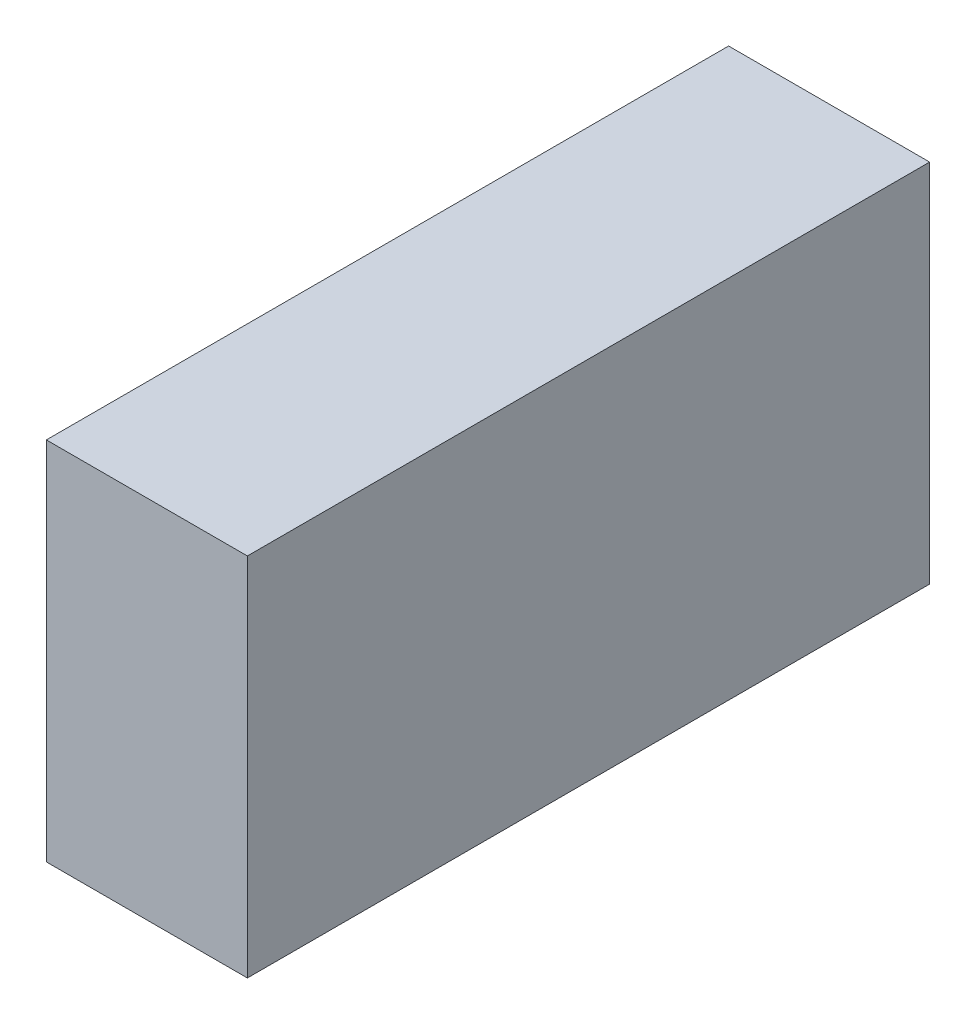
SolidWorks part; units mm, degrees
ref_plane "Front Plane" through (0, 0, 0) normal (1, 0, 0) x (0, 1, 0)
ref_plane "Top Plane" through (0, 0, 0) normal (0, 0, 1) x (0, 1, 0)
ref_plane "Right Plane" through (0, 0, 0) normal (0, 1, 0) x (-1, 0, 0)
sketch "Sketch1" plane through (0, 0, 0) normal (0, 0, 1) x (0, 1, 0)
  line L1 (-15, -8.25) -> (15, -8.25)
  line L2 (-15, -8.25) -> (-15, 8.25)
  line L3 (-15, 8.25) -> (15, 8.25)
  line L4 (15, -8.25) -> (15, 8.25)
  line L5 (-15, -8.25) -> (15, 8.25) construction
  line L6 (-15, 8.25) -> (15, -8.25) construction
  point P0 (0, 0)
  dimension "D1" = 30
  dimension "D2" = 16.5
extrude "Boss-Extrude1" add sketch "Sketch1" along normal blind 56
